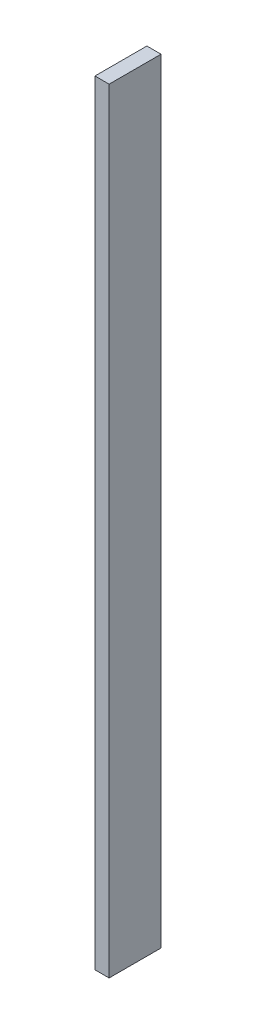
SolidWorks part; units mm, degrees
ref_plane "Front Plane" through (0, 0, 0) normal (0, 0, 1) x (1, 0, 0)
ref_plane "Top Plane" through (0, 0, 0) normal (0, 1, 0) x (1, 0, 0)
ref_plane "Right Plane" through (0, 0, 0) normal (1, 0, 0) x (0, 0, -1)
sketch "Sketch1" plane through (0, 0, 0) normal (0, 1, 0) x (1, 0, 0)
  line L1 (-19.05, -69.85) -> (19.05, -69.85)
  line L2 (-19.05, -69.85) -> (-19.05, 69.85)
  line L3 (-19.05, 69.85) -> (19.05, 69.85)
  line L4 (19.05, -69.85) -> (19.05, 69.85)
  line L5 (-19.05, -69.85) -> (19.05, 69.85) construction
  line L6 (-19.05, 69.85) -> (19.05, -69.85) construction
  point P0 (0, 0)
  dimension "D1" = 38.1
  dimension "D2" = 139.7
extrude "Boss-Extrude1" add sketch "Sketch1" along normal blind 2082.8
